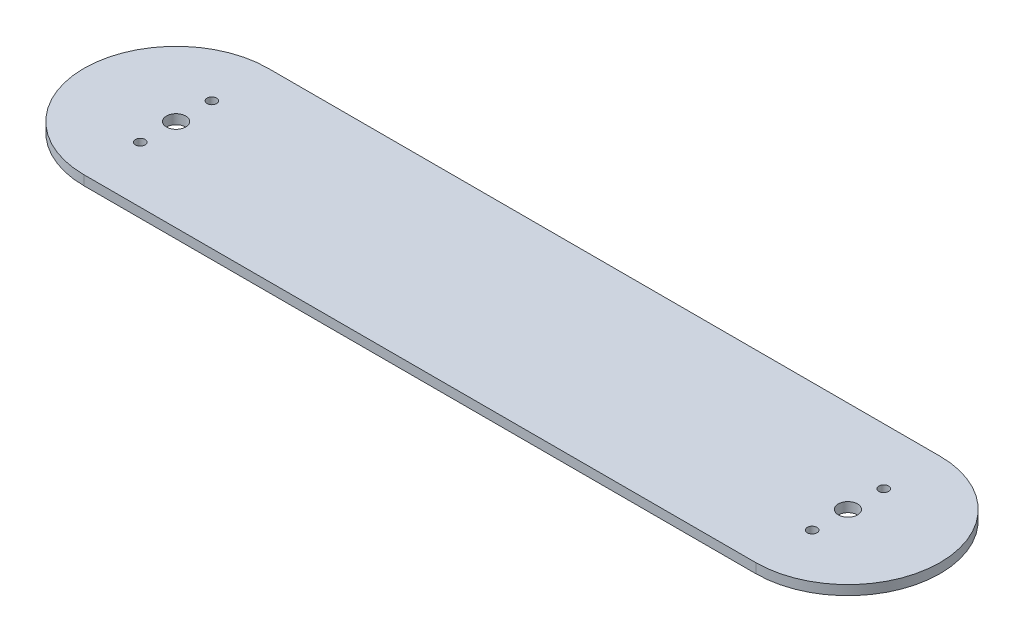
SolidWorks part; units mm, degrees
material "6061-T6 (SS)"
ref_plane "Front Plane" through (0, 0, 0) normal (0, 0, 1) x (1, 0, 0)
ref_plane "Top Plane" through (0, 0, 0) normal (0, 1, 0) x (1, 0, 0)
ref_plane "Right Plane" through (0, 0, 0) normal (1, 0, 0) x (0, 0, -1)
sketch "Sketch1" plane through (0, 0, 0) normal (0, 1, 0) x (1, 0, 0)
  line L0 (-175, 48) -> (175, 48)
  line L1 (0, 48) -> (0, -48) construction
  line L2 (175, -48) -> (-175, -48)
  arc A0 (-175, 48) -> (-175, -48) centre (-175, 0) ccw
  arc A1 (175, -48) -> (175, 48) centre (175, 0) ccw
  point P8 (0, 0)
  dimension "D1" = 96
  dimension "D2" = 350
extrude "Boss-Extrude1" add sketch "Sketch1" along normal blind 5
sketch "Sketch2" plane through (0, 0, 0) normal (0, -1, 0) x (1, 0, 0)
  line L0 (175, 0) -> (120, 0) construction
  line L1 (0, 48) -> (0, -48) construction
  line L2 (-175, 48) -> (175, 48) construction
  line L3 (175, -48) -> (-175, -48) construction
  line L4 (-175, 0) -> (-120, 0) construction
  circle A0 centre (175, 0) radius 5
  circle A1 centre (175, 18.65) radius 2.5
  circle A2 centre (175, -18.65) radius 2.5
  circle A5 centre (-175, -18.65) radius 2.5
  circle A6 centre (-175, 18.65) radius 2.5
  circle A7 centre (-175, 0) radius 5
  dimension "D1" = 10
  dimension "D2" = 5
  dimension "D3" = 18.65
  dimension "D4" = 37.3
  dimension "D5" = 55
extrude "Cut-Extrude1" cut sketch "Sketch2" against normal blind 10
